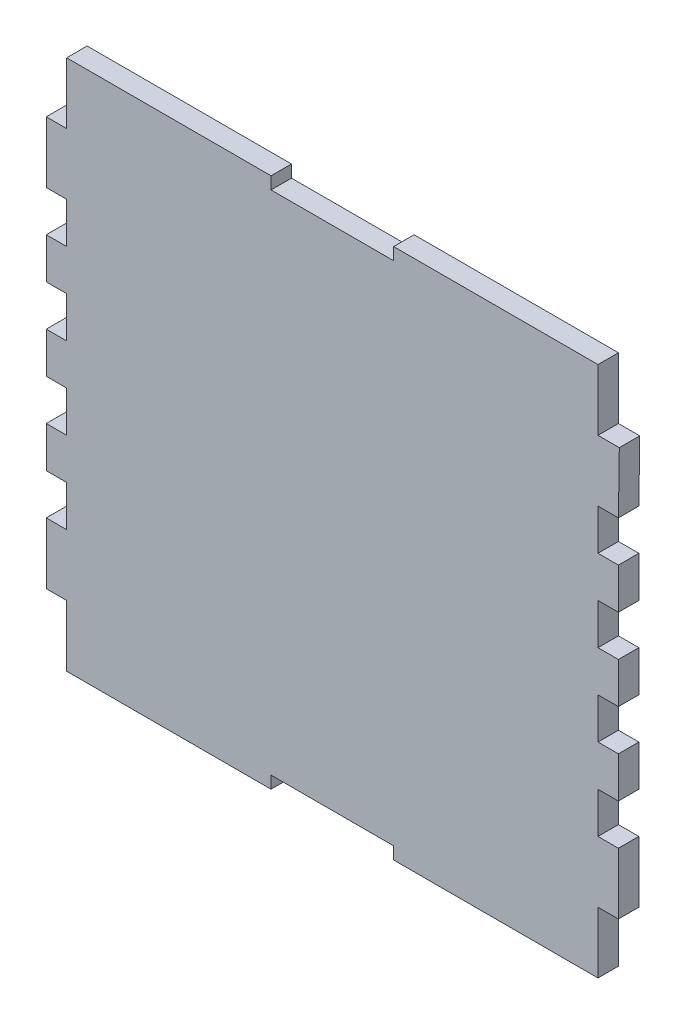
SolidWorks part; units mm, degrees
ref_plane "Front Plane" through (0, 0, 0) normal (0, 0, 1) x (1, 0, 0)
ref_plane "Top Plane" through (0, 0, 0) normal (0, 1, 0) x (1, 0, 0)
ref_plane "Right Plane" through (0, 0, 0) normal (1, 0, 0) x (0, 0, -1)
sketch "Sketch1" plane through (0, 0, 0) normal (0, 0, 1) x (1, 0, 0)
  line L0 (-44.809, -69.8705) -> (-34.809, -69.8705)
  line L1 (35.191, 60.1234) -> (45.191, 60.1234)
  line L2 (-44.809, 60.1234) -> (-34.809, 60.1234)
  line L3 (-54.809, 60.1234) -> (-64.809, 60.1234)
  line L4 (-64.809, -39.8705) -> (-64.809, -29.8705)
  line L5 (-54.809, 60.1234) -> (-44.809, 60.1234)
  line L6 (-64.809, -54.8705) -> (-64.809, -69.8705)
  line L7 (-34.809, 60.1234) -> (-24.809, 60.1234)
  line L8 (-54.809, -69.8705) -> (-44.809, -69.8705)
  line L9 (-64.809, 60.1234) -> (-64.809, 45.1234)
  line L10 (45.191, 60.1234) -> (55.191, 60.1234)
  line L11 (-34.809, -69.8705) -> (-24.809, -69.8705)
  line L12 (15.191, -69.8705) -> (25.191, -69.8705)
  line L13 (15.191, 60.1234) -> (25.191, 60.1234)
  line L14 (45.191, -69.8705) -> (55.191, -69.8705)
  line L15 (25.191, 60.1234) -> (35.191, 60.1234)
  line L16 (65.191, 60.1234) -> (65.191, 45.1234)
  line L17 (-69.809, 30.1234) -> (-64.809, 30.1295)
  line L18 (25.191, -69.8705) -> (35.191, -69.8705)
  line L19 (-64.809, 30.1295) -> (-64.809, 20.1295)
  line L20 (-69.809, 20.1295) -> (-64.809, 20.1295)
  line L21 (-14.809, 60.1234) -> (-14.809, 57.1234)
  line L22 (65.191, 30.1295) -> (70.191, 30.1295)
  line L23 (-14.809, -69.8705) -> (-14.809, -66.8705)
  line L24 (70.4072, 45.1234) -> (70.191, 30.1295)
  line L25 (-14.809, 57.1234) -> (15.191, 57.1234)
  line L26 (15.191, 57.1234) -> (15.191, 60.1234)
  line L27 (-14.809, -66.8705) -> (15.191, -66.8705)
  line L28 (15.191, -66.8705) -> (15.191, -69.8705)
  line L33 (55.191, 60.1234) -> (65.191, 60.1234)
  line L34 (35.191, -69.8705) -> (45.191, -69.8705)
  line L37 (55.191, -69.8705) -> (65.191, -69.8705)
  line L45 (-24.809, -69.8705) -> (-14.809, -69.8705)
  line L54 (-54.809, -69.8705) -> (-64.809, -69.8705)
  line L60 (-24.809, 60.1234) -> (-14.809, 60.1234)
  line L79 (-64.809, -54.8705) -> (-69.809, -54.8705)
  line L80 (-69.809, -54.8705) -> (-69.809, -39.8705)
  line L81 (-69.809, 0.1295) -> (-69.809, -9.8705)
  line L82 (-64.809, -39.8705) -> (-69.809, -39.8705)
  line L85 (-64.809, 45.1234) -> (-69.809, 45.1234)
  line L87 (-69.809, 45.1234) -> (-69.809, 30.1234)
  line L89 (-64.809, -29.8705) -> (-69.809, -29.8705)
  line L92 (-69.809, -29.8705) -> (-69.809, -19.8705)
  line L94 (-69.809, -19.8705) -> (-64.809, -19.8705)
  line L97 (-64.809, -19.8705) -> (-64.809, -9.8705)
  line L98 (-69.809, -9.8705) -> (-64.809, -9.8705)
  line L103 (-69.809, 0.1295) -> (-64.809, 0.1295)
  line L106 (-64.809, 0.1295) -> (-64.809, 10.1295)
  line L107 (-69.809, 10.1295) -> (-64.809, 10.1295)
  line L109 (-69.809, 10.1295) -> (-69.809, 20.1295)
  line L117 (70.191, -54.8705) -> (65.191, -54.8705)
  line L119 (70.191, -39.8705) -> (65.191, -39.8705)
  line L121 (70.4072, 45.1234) -> (65.191, 45.1234)
  line L123 (70.191, 20.1295) -> (70.191, 10.1295)
  line L125 (70.191, -29.8705) -> (65.191, -29.8705)
  line L130 (65.191, -19.8705) -> (70.191, -19.8705)
  line L134 (65.191, -9.8705) -> (70.191, -9.8705)
  line L136 (65.191, 0.1295) -> (70.191, 0.1295)
  line L143 (65.191, 10.1295) -> (70.191, 10.1295)
  line L148 (70.191, 20.1295) -> (65.191, 20.1295)
  line L152 (70.191, 0.1295) -> (70.191, -9.8705)
  line L153 (70.191, -19.8705) -> (70.191, -29.8705)
  line L154 (70.191, -54.8705) -> (70.191, -39.8705)
  line L155 (65.191, 30.1295) -> (65.191, 20.1295)
  line L156 (65.191, 10.1295) -> (65.191, 0.1295)
  line L158 (65.191, -9.8705) -> (65.191, -19.8705)
  line L159 (65.191, -29.8705) -> (65.191, -39.8705)
  line L160 (65.191, -54.8705) -> (65.191, -69.8705)
  point P0 (0, 0)
  dimension "D1" = 10
  dimension "D3" = 10
  dimension "D4" = 30
  dimension "D5" = 15
  dimension "D6" = 15
  dimension "D7" = 30
  dimension "D8" = 15
  dimension "D9" = 10
  dimension "D10" = 10
  dimension "D11" = 10
  dimension "D12" = 10
  dimension "D13" = 10
  dimension "D14" = 10
  dimension "D15" = 10
  dimension "D16" = 10
  dimension "D17" = 10
  dimension "D18" = 10
  dimension "D19" = 3
  dimension "D20" = 10
  dimension "D21" = 10
  dimension "D22" = 3
  dimension "D23" = 10
  dimension "D24" = 10
  dimension "D25" = 15
extrude "Boss-Extrude2" add sketch "Sketch1" along normal blind 5
